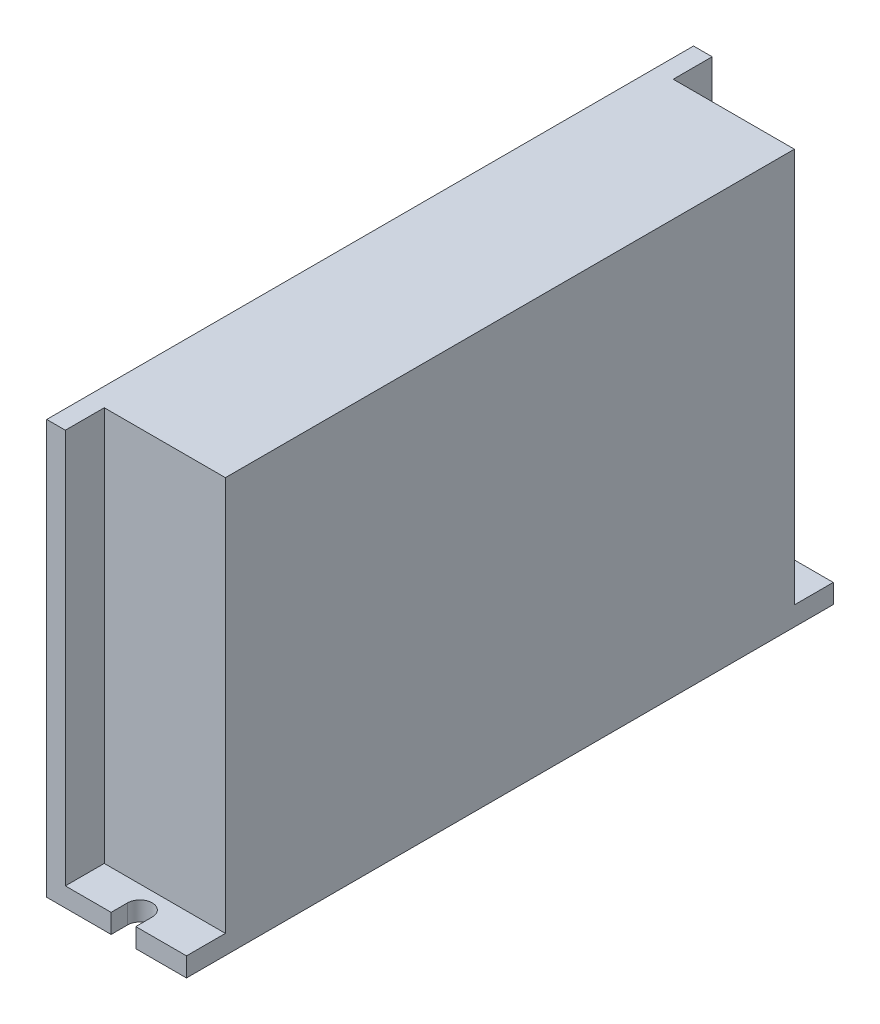
SolidWorks part; units mm, degrees
ref_plane "Front Plane" through (0, 0, 0) normal (0, 0, 1) x (1, 0, 0)
ref_plane "Top Plane" through (0, 0, 0) normal (0, 1, 0) x (1, 0, 0)
ref_plane "Right Plane" through (0, 0, 0) normal (1, 0, 0) x (0, 0, -1)
sketch "Sketch2" plane through (0, 0, 0) normal (0, 1, 0) x (1, 0, 0)
  line L1 (-12.75, -59) -> (12.75, -59)
  line L2 (-12.75, -59) -> (-12.75, 59)
  line L3 (-12.75, 59) -> (12.75, 59)
  line L4 (12.75, -59) -> (12.75, 59)
  line L5 (-12.75, -59) -> (12.75, 59) construction
  line L6 (-12.75, 59) -> (12.75, -59) construction
  point P0 (0, 0)
  dimension "D1" = 25.5
  dimension "D2" = 118
extrude "Boss-Extrude3" add sketch "Sketch2" along normal blind 3.5
sketch "Sketch3" plane through (0, 3.5, 0) normal (0, 1, 0) x (1, 0, 0)
  line L0 (12.75, 0) -> (-12.75, 0) construction
  line L1 (12.75, -59) -> (12.75, 59) construction
  line L2 (-12.75, 59) -> (-12.75, -59) construction
  line L3 (-12.75, -59) -> (12.75, -59) construction
  line L8 (-1, 56) -> (-1, 59)
  line L9 (12.75, 59) -> (-12.75, 59) construction
  line L10 (3.5, 56) -> (3.5, 59)
  line L11 (-1, -56) -> (-1, -59)
  line L12 (3.5, -56) -> (3.5, -59)
  line L13 (-1, 59) -> (3.5, 59)
  line L14 (-1, -59) -> (3.5, -59)
  arc A0 (3.5, -56) -> (-1, -56) centre (1.25, -56) ccw
  arc A1 (-1, 56) -> (3.5, 56) centre (1.25, 56) ccw
  dimension "D2" = 4.5
  dimension "D3" = 14
  dimension "D1" = 112
extrude "Cut-Extrude1" cut sketch "Sketch3" against normal through all
sketch "Sketch4" plane through (0, 3.5, 0) normal (0, 1, 0) x (1, 0, 0)
  line L0 (-12.75, -59) -> (-1, -59) construction
  line L1 (-12.75, 59) -> (-9.35, 59)
  line L2 (-12.75, 59) -> (-12.75, -59)
  line L3 (-12.75, -59) -> (-9.35, -59)
  line L4 (-9.35, 59) -> (-9.35, -59)
  dimension "D1" = 3.4
extrude "Boss-Extrude4" add sketch "Sketch4" along normal blind 72
sketch "Sketch5" plane through (0, 3.5, 0) normal (0, 1, 0) x (1, 0, 0)
  line L0 (12.75, 0) -> (-9.35, 0) construction
  line L1 (12.75, -59) -> (12.75, 59) construction
  line L2 (-9.35, -59) -> (-9.35, 59) construction
  line L3 (12.75, 59) -> (3.5, 59) construction
  line L4 (-9.35, -51.9) -> (12.75, -51.9)
  line L5 (-9.35, -51.9) -> (-9.35, 51.9)
  line L6 (-9.35, 51.9) -> (12.75, 51.9)
  line L7 (12.75, -51.9) -> (12.75, 51.9)
  line L8 (-9.35, -51.9) -> (12.75, 51.9) construction
  line L9 (-9.35, 51.9) -> (12.75, -51.9) construction
  point P6 (1.7, 0)
  dimension "D1" = 7.1
extrude "Boss-Extrude5" add sketch "Sketch5" along normal blind 72
